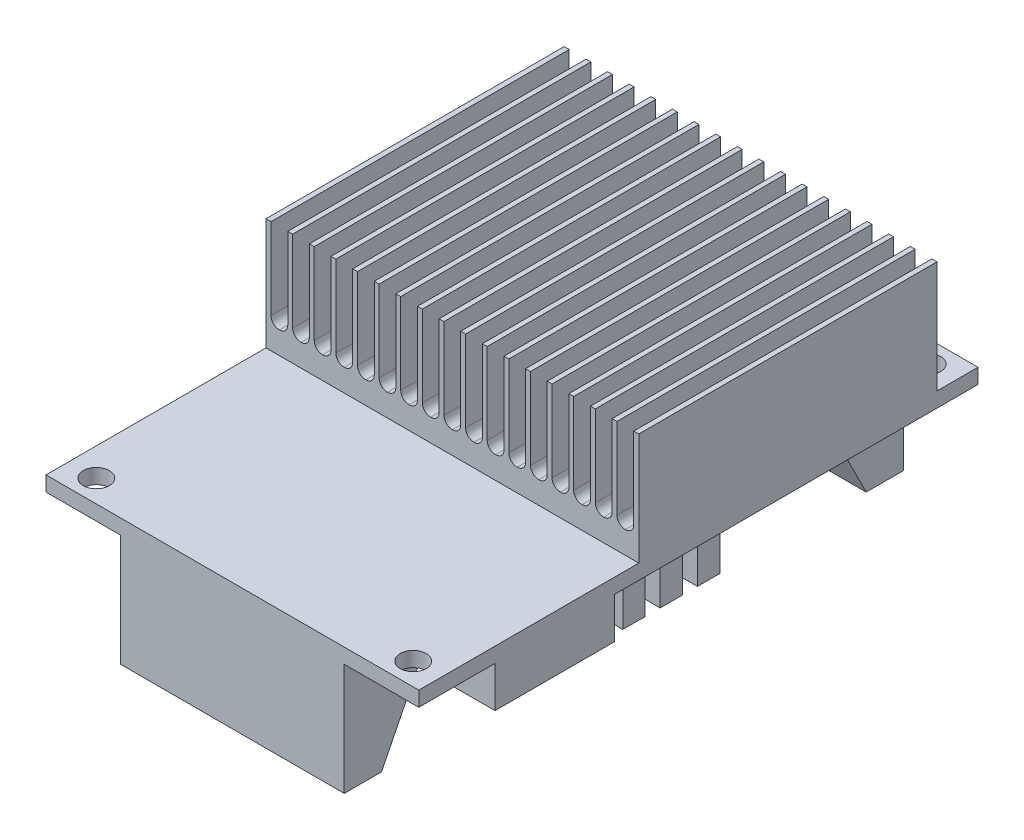
SolidWorks part; units mm, degrees
ref_plane "Front Plane" through (0, 0, 0) normal (0, 0, 1) x (1, 0, 0)
ref_plane "Top Plane" through (0, 0, 0) normal (0, 1, 0) x (1, 0, 0)
ref_plane "Right Plane" through (0, 0, 0) normal (1, 0, 0) x (0, 0, -1)
sketch "Sketch1" plane through (0, 0, 0) normal (0, 1, 0) x (1, 0, 0)
  line L1 (-25, 37.5) -> (25, 37.5)
  line L2 (-25, 37.5) -> (-25, -37.5)
  line L3 (-25, -37.5) -> (25, -37.5)
  line L4 (25, 37.5) -> (25, -37.5)
  line L5 (-25, 37.5) -> (25, -37.5) construction
  line L6 (-25, -37.5) -> (25, 37.5) construction
  point P0 (0, 0)
  dimension "D1" = 75
  dimension "D2" = 50
extrude "Boss-Extrude1" add sketch "Sketch1" along normal blind 2
sketch "Sketch2" plane through (0, 2, 0) normal (0, 1, 0) x (1, 0, 0)
  line L0 (0, 0) -> (0, 12) construction
  line L2 (-25, 32) -> (25, 32)
  line L3 (-25, 32) -> (-25, -8)
  line L4 (-25, -8) -> (25, -8)
  line L5 (25, 32) -> (25, -8)
  line L6 (-25, 32) -> (25, -8) construction
  line L7 (-25, -8) -> (25, 32) construction
  dimension "D1" = 12
  dimension "D2" = 40
  dimension "D3" = 50
extrude "Boss-Extrude2" add sketch "Sketch2" along normal blind 15
sketch "Sketch3" plane through (0, 0, -32) normal (0, 0, -1) x (-1, 0, 0)
  line L0 (0, 0) -> (0, 15) construction
  line L1 (4.025, 25) -> (4.025, 6.1)
  line L2 (-1.125, 25) -> (1.125, 25)
  line L3 (-1.125, 25) -> (-1.125, 6.1)
  line L4 (-0.025, 5) -> (0.025, 5)
  line L5 (1.125, 25) -> (1.125, 6.1)
  line L6 (-1.125, 25) -> (1.125, 5) construction
  line L7 (-1.125, 5) -> (1.125, 25) construction
  line L8 (1.775, 25) -> (4.025, 25)
  line L9 (1.775, 25) -> (1.775, 6.1)
  line L10 (2.875, 5) -> (2.925, 5)
  line L11 (6.925, 25) -> (6.925, 6.1)
  line L12 (4.675, 25) -> (6.925, 25)
  line L13 (4.675, 25) -> (4.675, 6.1)
  line L14 (5.775, 5) -> (5.825, 5)
  line L15 (9.825, 25) -> (9.825, 6.1)
  line L16 (7.575, 25) -> (9.825, 25)
  line L17 (7.575, 25) -> (7.575, 6.1)
  line L18 (8.675, 5) -> (8.725, 5)
  line L19 (12.725, 25) -> (12.725, 6.1)
  line L20 (10.475, 25) -> (12.725, 25)
  line L21 (10.475, 25) -> (10.475, 6.1)
  line L22 (11.575, 5) -> (11.625, 5)
  line L23 (15.625, 25) -> (15.625, 6.1)
  line L24 (13.375, 25) -> (15.625, 25)
  line L25 (13.375, 25) -> (13.375, 6.1)
  line L26 (14.475, 5) -> (14.525, 5)
  line L27 (18.525, 25) -> (18.525, 6.1)
  line L28 (16.275, 25) -> (18.525, 25)
  line L29 (16.275, 25) -> (16.275, 6.1)
  line L30 (17.375, 5) -> (17.425, 5)
  line L31 (21.425, 25) -> (21.425, 6.1)
  line L32 (19.175, 25) -> (21.425, 25)
  line L33 (19.175, 25) -> (19.175, 6.1)
  line L34 (20.275, 5) -> (20.325, 5)
  line L35 (24.325, 25) -> (24.325, 6.1)
  line L36 (22.075, 25) -> (24.325, 25)
  line L37 (22.075, 25) -> (22.075, 6.1)
  line L38 (23.175, 5) -> (23.225, 5)
  line L39 (-1.775, 25) -> (-1.775, 6.1)
  line L40 (-4.025, 25) -> (-1.775, 25)
  line L41 (-4.025, 25) -> (-4.025, 6.1)
  line L42 (-2.925, 5) -> (-2.875, 5)
  line L43 (-4.675, 25) -> (-4.675, 6.1)
  line L44 (-6.925, 25) -> (-4.675, 25)
  line L45 (-6.925, 25) -> (-6.925, 6.1)
  line L46 (-5.825, 5) -> (-5.775, 5)
  line L47 (-7.575, 25) -> (-7.575, 6.1)
  line L48 (-9.825, 25) -> (-7.575, 25)
  line L49 (-9.825, 25) -> (-9.825, 6.1)
  line L50 (-8.725, 5) -> (-8.675, 5)
  line L51 (-10.475, 25) -> (-10.475, 6.1)
  line L52 (-12.725, 25) -> (-10.475, 25)
  line L53 (-12.725, 25) -> (-12.725, 6.1)
  line L54 (-11.625, 5) -> (-11.575, 5)
  line L55 (-13.375, 25) -> (-13.375, 6.1)
  line L56 (-15.625, 25) -> (-13.375, 25)
  line L57 (-15.625, 25) -> (-15.625, 6.1)
  line L58 (-14.525, 5) -> (-14.475, 5)
  line L59 (-16.275, 25) -> (-16.275, 6.1)
  line L60 (-18.525, 25) -> (-16.275, 25)
  line L61 (-18.525, 25) -> (-18.525, 6.1)
  line L62 (-17.425, 5) -> (-17.375, 5)
  line L63 (-19.175, 25) -> (-19.175, 6.1)
  line L64 (-21.425, 25) -> (-19.175, 25)
  line L65 (-21.425, 25) -> (-21.425, 6.1)
  line L66 (-20.325, 5) -> (-20.275, 5)
  line L67 (-22.075, 25) -> (-22.075, 6.1)
  line L68 (-24.325, 25) -> (-22.075, 25)
  line L69 (-24.325, 25) -> (-24.325, 6.1)
  line L70 (-23.225, 5) -> (-23.175, 5)
  arc A0 (0.025, 5) -> (1.125, 6.1) centre (0.025, 6.1) ccw
  arc A1 (-1.125, 6.1) -> (-0.025, 5) centre (-0.025, 6.1) ccw
  arc A2 (1.775, 6.1) -> (2.875, 5) centre (2.875, 6.1) ccw
  arc A3 (2.925, 5) -> (4.025, 6.1) centre (2.925, 6.1) ccw
  arc A4 (4.675, 6.1) -> (5.775, 5) centre (5.775, 6.1) ccw
  arc A5 (5.825, 5) -> (6.925, 6.1) centre (5.825, 6.1) ccw
  arc A6 (7.575, 6.1) -> (8.675, 5) centre (8.675, 6.1) ccw
  arc A7 (8.725, 5) -> (9.825, 6.1) centre (8.725, 6.1) ccw
  arc A8 (10.475, 6.1) -> (11.575, 5) centre (11.575, 6.1) ccw
  arc A9 (11.625, 5) -> (12.725, 6.1) centre (11.625, 6.1) ccw
  arc A10 (13.375, 6.1) -> (14.475, 5) centre (14.475, 6.1) ccw
  arc A11 (14.525, 5) -> (15.625, 6.1) centre (14.525, 6.1) ccw
  arc A12 (16.275, 6.1) -> (17.375, 5) centre (17.375, 6.1) ccw
  arc A13 (17.425, 5) -> (18.525, 6.1) centre (17.425, 6.1) ccw
  arc A14 (19.175, 6.1) -> (20.275, 5) centre (20.275, 6.1) ccw
  arc A15 (20.325, 5) -> (21.425, 6.1) centre (20.325, 6.1) ccw
  arc A16 (22.075, 6.1) -> (23.175, 5) centre (23.175, 6.1) ccw
  arc A17 (23.225, 5) -> (24.325, 6.1) centre (23.225, 6.1) ccw
  arc A18 (-4.025, 6.1) -> (-2.925, 5) centre (-2.925, 6.1) ccw
  arc A19 (-2.875, 5) -> (-1.775, 6.1) centre (-2.875, 6.1) ccw
  arc A20 (-6.925, 6.1) -> (-5.825, 5) centre (-5.825, 6.1) ccw
  arc A21 (-5.775, 5) -> (-4.675, 6.1) centre (-5.775, 6.1) ccw
  arc A22 (-9.825, 6.1) -> (-8.725, 5) centre (-8.725, 6.1) ccw
  arc A23 (-8.675, 5) -> (-7.575, 6.1) centre (-8.675, 6.1) ccw
  arc A24 (-12.725, 6.1) -> (-11.625, 5) centre (-11.625, 6.1) ccw
  arc A25 (-11.575, 5) -> (-10.475, 6.1) centre (-11.575, 6.1) ccw
  arc A26 (-15.625, 6.1) -> (-14.525, 5) centre (-14.525, 6.1) ccw
  arc A27 (-14.475, 5) -> (-13.375, 6.1) centre (-14.475, 6.1) ccw
  arc A28 (-18.525, 6.1) -> (-17.425, 5) centre (-17.425, 6.1) ccw
  arc A29 (-17.375, 5) -> (-16.275, 6.1) centre (-17.375, 6.1) ccw
  arc A30 (-21.425, 6.1) -> (-20.325, 5) centre (-20.325, 6.1) ccw
  arc A31 (-20.275, 5) -> (-19.175, 6.1) centre (-20.275, 6.1) ccw
  arc A32 (-24.325, 6.1) -> (-23.225, 5) centre (-23.225, 6.1) ccw
  arc A33 (-23.175, 5) -> (-22.075, 6.1) centre (-23.175, 6.1) ccw
  dimension "D3" = 1.1
  dimension "D1" = 20
  dimension "D2" = 2.25
  dimension "D4" = 9
  dimension "D5" = 9
extrude "Cut-Extrude1" cut sketch "Sketch3" against normal up to surface (40 mm away) up to face at (0, 9.5, 8)
sketch "Sketch4" plane through (0, 0, 0) normal (0, -1, 0) x (1, 0, 0)
  line L0 (0, 37.5) -> (0, 27.5) construction
  line L1 (-25, 37.5) -> (25, 37.5) construction
  line L2 (0, 0) -> (25, 0) construction
  line L3 (-15, 37.5) -> (15, 37.5)
  line L4 (-15, 37.5) -> (-15, 27.5)
  line L5 (-15, 27.5) -> (15, 27.5)
  line L6 (15, 37.5) -> (15, 27.5)
  line L7 (-15, 37.5) -> (15, 27.5) construction
  line L8 (-15, 27.5) -> (15, 37.5) construction
  line L9 (25, 37.5) -> (25, -37.5) construction
  line L10 (-15, -27.5) -> (15, -37.5) construction
  line L11 (-15, -37.5) -> (15, -27.5) construction
  line L12 (0, -37.5) -> (0, -27.5) construction
  line L13 (15, -37.5) -> (15, -27.5)
  line L14 (-15, -27.5) -> (15, -27.5)
  line L15 (-15, -37.5) -> (-15, -27.5)
  line L16 (-15, -37.5) -> (15, -37.5)
  point P5 (0, 32.5)
  point P20 (0, -32.5)
  dimension "D1" = 10
  dimension "D2" = 30
  dimension "D3" = 10
extrude "Boss-Extrude3" add sketch "Sketch4" along normal blind 15
sketch "Sketch5" plane through (-15, 0, 0) normal (-1, 0, 0) x (0, 0, 1)
  line L0 (-27.5, -15) -> (-27.5, -5)
  line L1 (-27.5, -15) -> (-27.5, 0) construction
  line L2 (-27.5, -5) -> (-32.5, -15)
  line L3 (-27.5, -15) -> (-37.5, -15) construction
  line L4 (-32.5, -15) -> (-27.5, -15)
  line L5 (0, 0) -> (0, -15) construction
  line L6 (32.5, -15) -> (27.5, -15)
  line L7 (27.5, -5) -> (32.5, -15)
  line L8 (27.5, -15) -> (27.5, -5)
  dimension "D1" = 10
extrude "Cut-Extrude2" cut sketch "Sketch5" against normal blind 30
sketch "Sketch6" plane through (0, 0, 0) normal (0, -1, 0) x (1, 0, 0)
  line L0 (0, 0) -> (0, -27.5) construction
  line L1 (15, -27.5) -> (-15, -27.5) construction
  line L2 (0, -27.5) -> (-20, -27.5) construction
  circle A0 centre (-20, -27.5) radius 4.75
  dimension "D1" = 9.5
  dimension "D2" = 20
extrude "Boss-Extrude6" add sketch "Sketch6" along normal blind 17
sketch "Sketch7" plane through (0, 0, 0) normal (0, -1, 0) x (1, 0, 0)
  line L0 (25, 37.5) -> (25, -37.5) construction
  line L1 (15.28, 27.2748) -> (25, 27.2748)
  line L2 (15.28, 27.2748) -> (15.28, 11.2748)
  line L3 (15.28, 11.2748) -> (25, 11.2748)
  line L4 (25, 27.2748) -> (25, 11.2748)
  dimension "D1" = 16
  dimension "D2" = 9.72
extrude "Boss-Extrude9" add sketch "Sketch7" along normal blind 5.5
sketch "Sketch8" plane through (0, 0, 0) normal (0, -1, 0) x (-1, 0, 0)
  line L0 (-20.14, -11.2748) -> (-20.14, -8.2748) construction
  line L1 (-15.28, -11.2748) -> (-25, -11.2748) construction
  line L2 (-15.64, -1.7748) -> (-24.64, -1.7748)
  line L3 (-15.64, -9.7748) -> (-24.64, -9.7748)
  line L4 (-15.64, -9.7748) -> (-15.64, -6.7748)
  line L5 (-15.64, -6.7748) -> (-24.64, -6.7748)
  line L6 (-24.64, -9.7748) -> (-24.64, -6.7748)
  line L7 (-15.64, -9.7748) -> (-24.64, -6.7748) construction
  line L8 (-15.64, -6.7748) -> (-24.64, -9.7748) construction
  line L9 (-15.64, -4.7748) -> (-15.64, -1.7748)
  line L10 (-15.64, -4.7748) -> (-24.64, -4.7748)
  line L11 (-24.64, -4.7748) -> (-24.64, -1.7748)
  line L12 (-15.64, 3.2252) -> (-24.64, 3.2252)
  line L13 (-15.64, 0.2252) -> (-15.64, 3.2252)
  line L14 (-15.64, 0.2252) -> (-24.64, 0.2252)
  line L15 (-24.64, 0.2252) -> (-24.64, 3.2252)
  dimension "D1" = 3
  dimension "D2" = 3
  dimension "D3" = 9
  dimension "D4" = 3
extrude "Boss-Extrude10" add sketch "Sketch8" along normal blind 5
sketch "Sketch9" plane through (0, 2, 0) normal (0, 1, 0) x (1, 0, 0)
  line L1 (-21.25, 34.5) -> (21.25, 34.5) construction
  line L2 (-21.25, 34.5) -> (-21.25, -34.5) construction
  line L3 (-21.25, -34.5) -> (21.25, -34.5) construction
  line L4 (21.25, 34.5) -> (21.25, -34.5) construction
  line L5 (-21.25, 34.5) -> (21.25, -34.5) construction
  line L6 (-21.25, -34.5) -> (21.25, 34.5) construction
  circle A0 centre (-21.25, 34.5) radius 1.75
  circle A1 centre (21.25, 34.5) radius 1.75
  circle A2 centre (-21.25, -34.5) radius 1.75
  circle A3 centre (21.25, -34.5) radius 1.75
  point P0 (0, 0)
  dimension "D3" = 3.5
  dimension "D4" = 3.5
  dimension "D5" = 3.5
  dimension "D6" = 3.5
  dimension "D1" = 69
  dimension "D2" = 42.5
extrude "Cut-Extrude4" cut sketch "Sketch9" against normal blind 2
